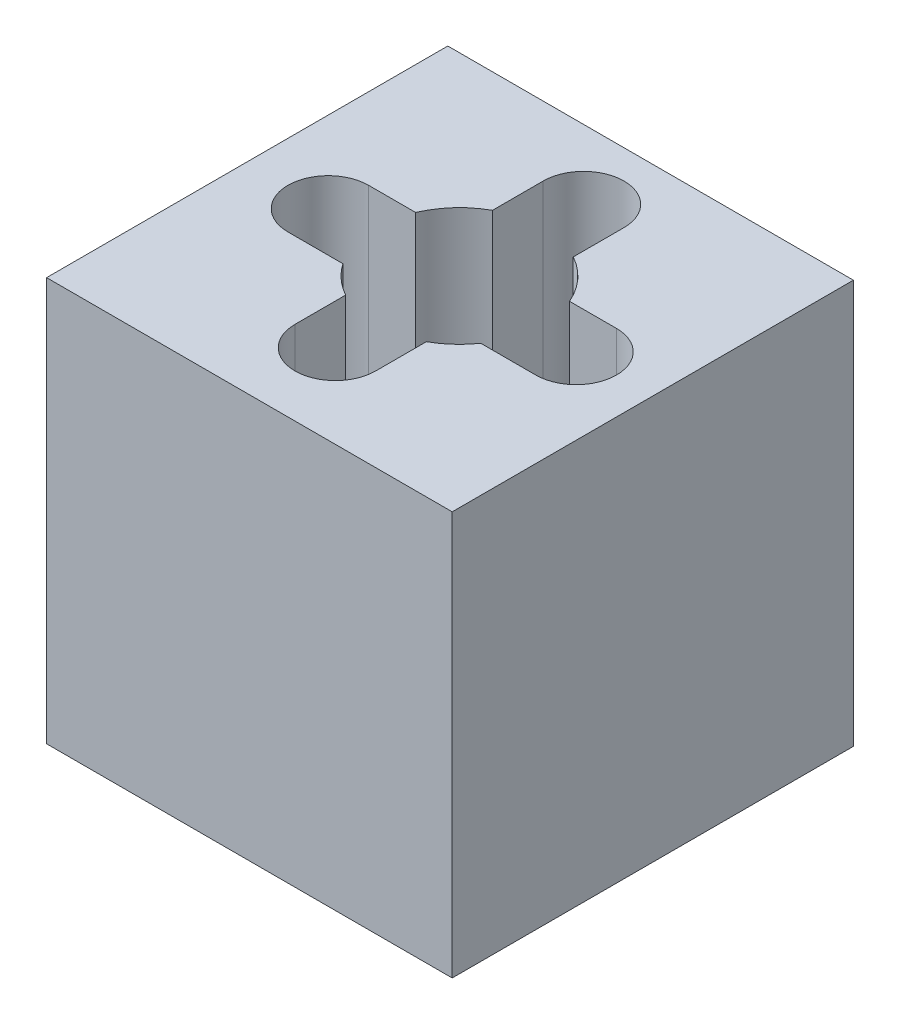
SolidWorks part; units mm, degrees
ref_plane "Front Plane" through (0, 0, 0) normal (0, 0, 1) x (1, 0, 0)
ref_plane "Top Plane" through (0, 0, 0) normal (0, 1, 0) x (1, 0, 0)
ref_plane "Right Plane" through (0, 0, 0) normal (1, 0, 0) x (0, 0, -1)
sketch "Sketch1" plane through (0, 0, 0) normal (0, 1, 0) x (1, 0, 0)
  line L0 (-1.5594, -0.5993) -> (-0.8671, -0.5993)
  line L1 (0, 1.0541) -> (0, -1.0541) construction
  line L2 (-1.5594, 0.4167) -> (-0.9683, 0.4167)
  line L4 (-2.5795, -0.0913) -> (-2.5795, 2.4327)
  line L5 (-2.5795, 2.4327) -> (2.524, 2.4327)
  line L6 (2.524, -0.0913) -> (2.524, 2.4327)
  line L8 (-2.5795, -0.0913) -> (-2.5795, -2.6154)
  line L9 (-2.5795, -2.6154) -> (2.524, -2.6154)
  line L10 (2.524, -0.0913) -> (2.524, -2.6154)
  line L11 (-0.508, 1.5621) -> (-0.508, 0.9236)
  line L12 (0.508, 1.5621) -> (0.508, 0.9236)
  line L13 (1.5594, 0.4167) -> (0.9683, 0.4167)
  line L14 (1.5594, -0.5993) -> (0.8671, -0.5993)
  line L15 (-0.508, -1.5621) -> (-0.508, -0.9236)
  line L16 (0.508, -1.5621) -> (0.508, -0.9236)
  arc A0 (0.9683, 0.4167) -> (0.508, 0.9236) centre (0, 0) ccw
  arc A1 (1.5594, -0.5993) -> (1.5594, 0.4167) centre (1.5594, -0.0913) ccw
  arc A2 (0.508, 1.5621) -> (-0.508, 1.5621) centre (0, 1.5621) ccw
  arc A3 (0.508, -1.5621) -> (-0.508, -1.5621) centre (0, -1.5621) cw
  arc A4 (-1.5594, -0.5993) -> (-1.5594, 0.4167) centre (-1.5594, -0.0913) cw
  arc A5 (-0.508, 0.9236) -> (-0.9683, 0.4167) centre (0, 0) ccw
  arc A6 (-0.8671, -0.5993) -> (-0.508, -0.9236) centre (0, 0) ccw
  arc A7 (0.508, -0.9236) -> (0.8671, -0.5993) centre (0, 0) ccw
  point P6 (0, 0)
  dimension "D1" = 2.1082
  dimension "D2" = 1.016
extrude "Boss-Extrude1" add sketch "Sketch1" along normal blind 5.08
